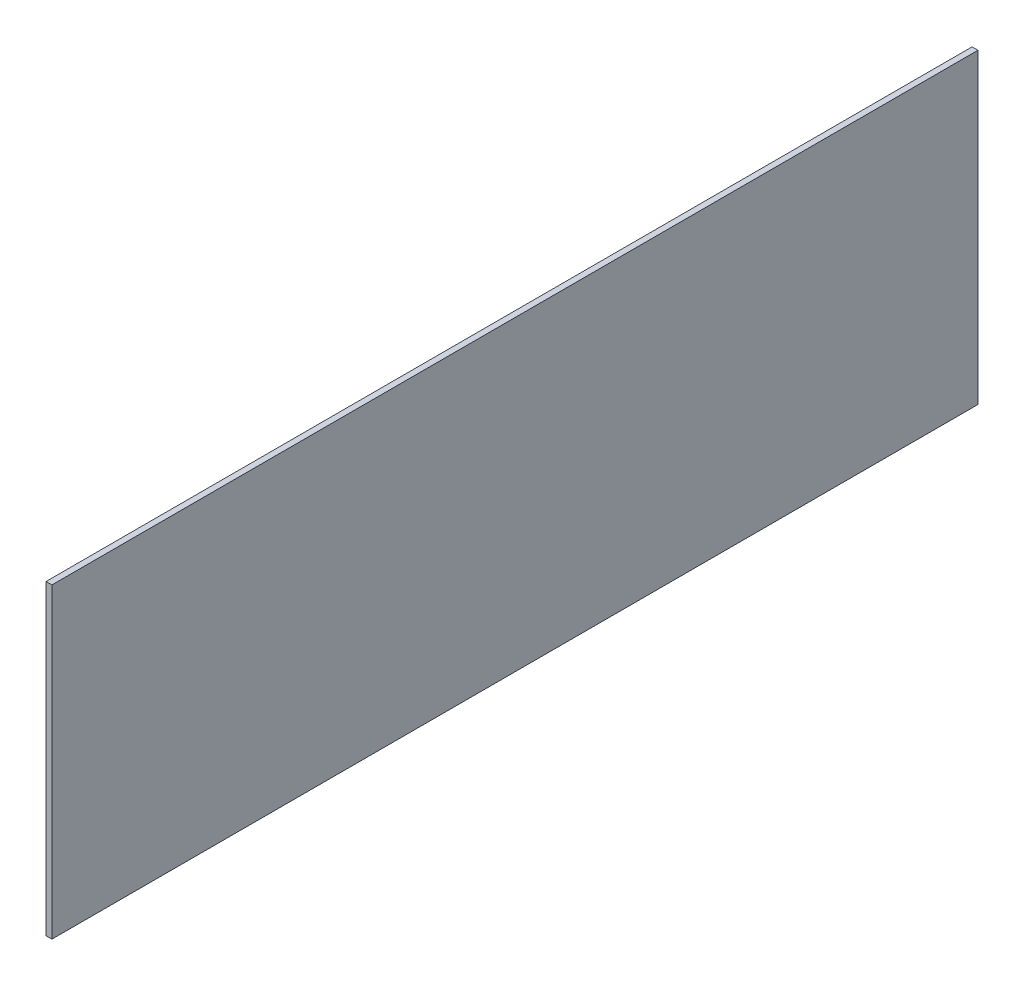
SolidWorks part; units mm, degrees
material "6061-T6 (SS)"
ref_plane "X-Y Datum" through (0, 0, 0) normal (0, 0, 1) x (1, 0, 0)
ref_plane "X-Z Datum" through (0, 0, 0) normal (0, 1, 0) x (1, 0, 0)
ref_plane "Y-Z Datum" through (0, 0, 0) normal (1, 0, 0) x (0, 0, -1)
sketch "Sketch1" plane through (0, 0, 0) normal (1, 0, 0) x (0, 0, -1)
  line L1 (-249.174, 82.55) -> (249.174, 82.55)
  line L2 (-249.174, 82.55) -> (-249.174, -82.55)
  line L3 (-249.174, -82.55) -> (249.174, -82.55)
  line L4 (249.174, 82.55) -> (249.174, -82.55)
  line L5 (-249.174, 82.55) -> (249.174, -82.55) construction
  line L6 (-249.174, -82.55) -> (249.174, 82.55) construction
  point P0 (0, 0)
  dimension "D1" = 165.1
  dimension "D2" = 498.348
extrude "Boss-Extrude1" add sketch "Sketch1" along normal mid plane 3.175
